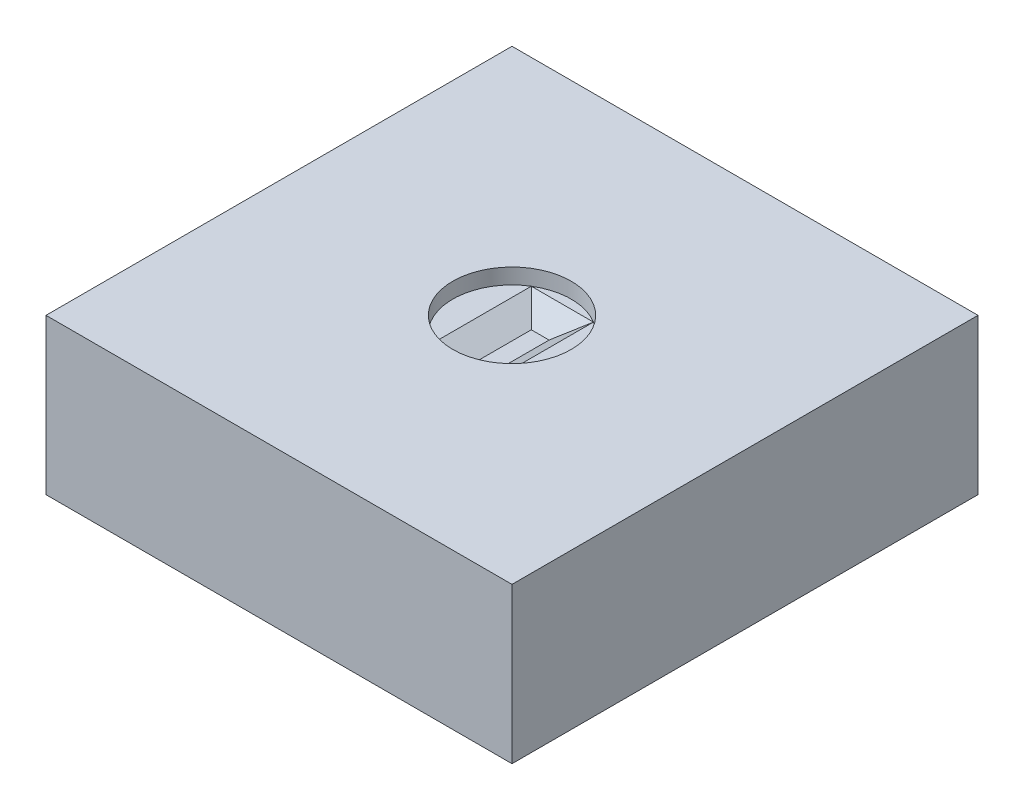
SolidWorks part; units mm, degrees
ref_plane "Front Plane" through (0, 0, 0) normal (0, 0, 1) x (1, 0, 0)
ref_plane "Top Plane" through (0, 0, 0) normal (0, 1, 0) x (1, 0, 0)
ref_plane "Right Plane" through (0, 0, 0) normal (1, 0, 0) x (0, 0, -1)
sketch "Sketch1" plane through (0, 0, 0) normal (0, 1, 0) x (1, 0, 0)
  line L1 (0, 15) -> (0, -15) construction
  line L2 (-15, 0) -> (15, 0) construction
  line L3 (-15, -15) -> (15, -15)
  line L4 (-15, -15) -> (-15, 15)
  line L5 (-15, 15) -> (15, 15)
  line L6 (15, -15) -> (15, 15)
  circle A0 centre (0, 0) radius 15
  point P3 (0, 0)
  dimension "D1" = 30
extrude "Boss-Extrude1" add sketch "Sketch1" along normal blind 10
sketch "Sketch2" plane through (0, 10, 0) normal (0, 1, 0) x (1, 0, 0)
  circle A0 centre (0, 0) radius 3.81
  point P8 (0, 0)
  dimension "D1" = 7.62
extrude "bore" cut sketch "Sketch2" against normal blind 1
sketch "Sketch3" plane through (0, 9, 0) normal (0, 1, 0) x (1, 0, 0)
  line L0 (-2, 3.2429) -> (2, 3.2429)
  line L1 (-2, 3.2429) -> (-2, -3.2429)
  line L2 (2, 3.2429) -> (2, -3.2429)
  line L3 (-2, -3.2429) -> (2, -3.2429)
  line L4 (0, 3.2429) -> (0, -3.2429) construction
  circle A0 centre (0, 0) radius 3.81 construction
  point P11 (0, 0)
  dimension "D1" = 4
extrude "groove" cut sketch "Sketch3" against normal blind 1 draft 55
sketch "Sketch4" plane through (0, 8, 0) normal (0, 1, 0) x (1, 0, 0)
  line L0 (0, 1.8147) -> (0, -1.8147) construction
  line L1 (0.5719, 1.8147) -> (-0.5719, 1.8147) construction
  line L2 (-0.5719, -1.8147) -> (0.5719, -1.8147) construction
  line L3 (-0.5719, 0) -> (0.5719, 0) construction
  line L4 (-0.5719, 1.8147) -> (-0.5719, -1.8147) construction
  line L5 (0.5719, -1.8147) -> (0.5719, 1.8147) construction
  circle A0 centre (0, 0) radius 0.5719
extrude "seat for screw" [suppressed] cut sketch "Sketch4" against normal blind 0.1 draft 58
equation "\"draft angle\"= 65deg"
equation "\"D3\"= \"draft angle\""
equation "\"altitude\"= cotan ( \"draft angle\" ) * 3 / 2 * .25in"
equation "\"D1\"= 15"
equation "\"D1@Sketch1\"=\"foot diam@table assembly.Assembly\""
equation "\"D1@Sketch2\"=\"bore diam@table assembly.Assembly\""
equation "\"D1@Boss-Extrude1\"=\"foot height@table assembly.Assembly\""
equation "\"D1@Sketch3\"=4"
